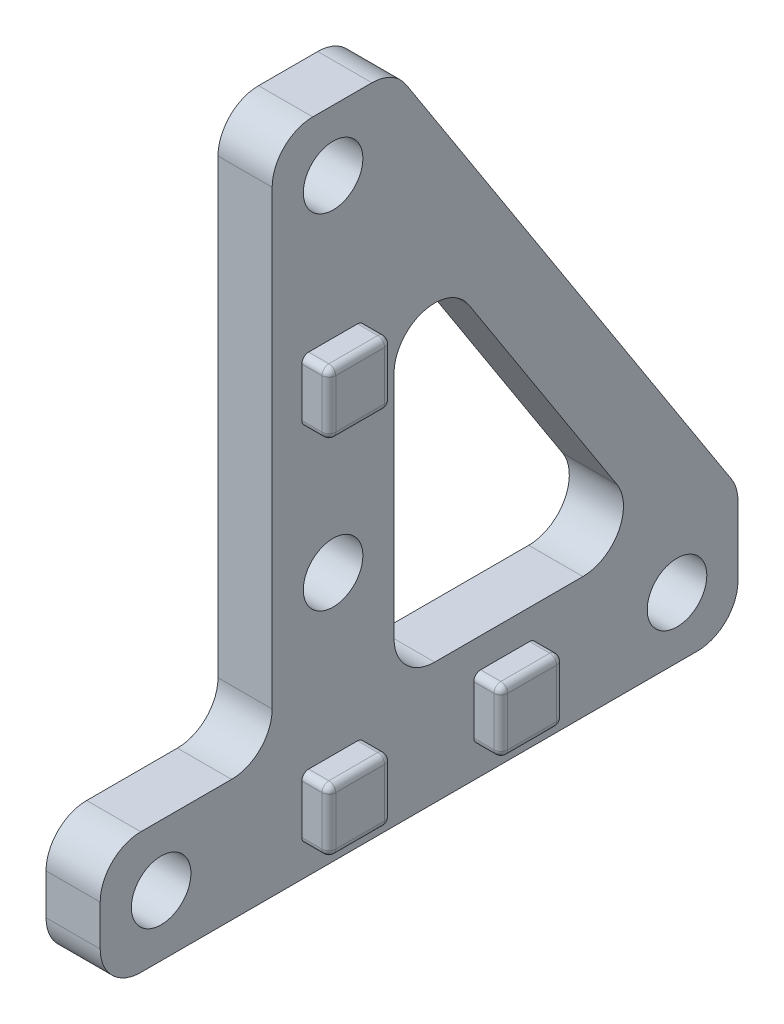
SolidWorks part; units mm, degrees
ref_plane "Front Plane" through (0, 0, 0) normal (0, 0, 1) x (1, 0, 0)
ref_plane "Top Plane" through (0, 0, 0) normal (0, 1, 0) x (1, 0, 0)
ref_plane "Right Plane" through (0, 0, 0) normal (1, 0, 0) x (0, 0, -1)
sketch "Sketch1" plane through (0, 0, 0) normal (1, 0, 0) x (0, 0, -1)
  line L0 (-4.5, 4.5) -> (-17.2, 4.5)
  line L1 (-17.2, 4.5) -> (-17.2, -4.5)
  line L2 (-17.2, -4.5) -> (29.9, -4.5)
  line L3 (29.9, -4.5) -> (29.9, 4.5)
  line L4 (29.9, 4.5) -> (4.5, 43.87)
  line L5 (4.5, 43.87) -> (-4.5, 43.87)
  line L6 (-4.5, 43.87) -> (-4.5, 4.5)
  line L7 (4.5, 4.5) -> (23.9497, 4.5)
  line L8 (23.9497, 4.5) -> (4.5, 34.6471)
  line L9 (4.5, 34.6471) -> (4.5, 4.5)
  circle A1 centre (25.4, 0) radius 2.2
  circle A2 centre (0, 13.97) radius 2.2
  circle A3 centre (0, 39.37) radius 2.2
  circle A4 centre (-12.7, 0) radius 2.2
  dimension "D1" = 4.4
  dimension "D2" = 12.7
  dimension "D3" = 25.4
  dimension "D4" = 13.97
  dimension "D5" = 25.4
  dimension "D6" = 4.5
  dimension "D7" = 4.5
  dimension "D8" = 4.5
  dimension "D9" = 9
  dimension "D10" = 4.5
  dimension "D11" = 4.5
  dimension "D12" = 9
  dimension "D13" = 9
  dimension "D14" = 5
extrude "Boss-Extrude1" add sketch "Sketch1" along normal blind 4
fillet "Fillet1" radius 3 10 edges at (2, 4.5, 4.5) (2, -4.5, 17.2) (2, 4.5, 17.2) (2, -4.5, -29.9) (2, 4.5, -29.9) (2, 43.87, -4.5) (2, 43.87, 4.5) (2, 4.5, -4.5) (2, 4.5, -23.9497) (2, 34.6471, -4.5)
sketch "Sketch2" plane through (4, 0, 0) normal (1, 0, 0) x (0, 0, -1)
  line L1 (2.3114, 2.3114) -> (-2.3114, 2.3114)
  line L2 (2.3114, 2.3114) -> (2.3114, -2.3114)
  line L3 (2.3114, -2.3114) -> (-2.3114, -2.3114)
  line L4 (-2.3114, 2.3114) -> (-2.3114, -2.3114)
  line L5 (2.3114, 2.3114) -> (-2.3114, -2.3114) construction
  line L6 (2.3114, -2.3114) -> (-2.3114, 2.3114) construction
  line L7 (15.0114, 2.3114) -> (10.3886, 2.3114)
  line L8 (15.0114, 2.3114) -> (15.0114, -2.3114)
  line L9 (15.0114, -2.3114) -> (10.3886, -2.3114)
  line L10 (10.3886, 2.3114) -> (10.3886, -2.3114)
  line L11 (15.0114, 2.3114) -> (10.3886, -2.3114) construction
  line L12 (15.0114, -2.3114) -> (10.3886, 2.3114) construction
  line L13 (-2.3114, 28.9814) -> (2.3114, 28.9814)
  line L14 (-2.3114, 28.9814) -> (-2.3114, 24.3586)
  line L15 (-2.3114, 24.3586) -> (2.3114, 24.3586)
  line L16 (2.3114, 28.9814) -> (2.3114, 24.3586)
  line L17 (-2.3114, 28.9814) -> (2.3114, 24.3586) construction
  line L18 (-2.3114, 24.3586) -> (2.3114, 28.9814) construction
  point P0 (0, 0)
  point P6 (12.7, 0)
  point P11 (0, 26.67)
  point P16 (0, 13.97)
  point P17 (0, 0)
  point P19 (0, 0)
  dimension "D1" = 12.7
  dimension "D2" = 12.7
  dimension "D3" = 4.6228
extrude "Boss-Extrude2" add sketch "Sketch2" along normal blind 2
fillet "Fillet2" radius 0.508 12 edges at (5, 2.3114, -15.0114) (5, 2.3114, -10.3886) (5, -2.3114, -10.3886) (5, -2.3114, -15.0114) (5, -2.3114, -2.3114) (5, 2.3114, -2.3114) (5, 2.3114, 2.3114) (5, -2.3114, 2.3114) (5, 28.9814, 2.3114) (5, 28.9814, -2.3114) (5, 24.3586, -2.3114) (5, 24.3586, 2.3114)
fillet "Fillet3" radius 0.508 24 edges at (6, -2.1626, -10.5374) (6, 0, -10.3886) (6, 2.1626, -10.5374) (6, 2.3114, -12.7) (6, 2.1626, -14.8626) (6, 0, -15.0114) (6, -2.1626, -14.8626) (6, -2.1626, 2.1626) (6, 0, 2.3114) (6, 2.1626, 2.1626) (6, 2.3114, 0) (6, 2.1626, -2.1626) (6, 0, -2.3114) (6, -2.1626, -2.1626) (6, 24.5074, 2.1626) (6, 26.67, 2.3114) (6, 28.8326, 2.1626) (6, 28.9814, 0) (6, 28.8326, -2.1626) (6, 26.67, -2.3114) (6, 24.5074, -2.1626) (6, -2.3114, -12.7) (6, -2.3114, 0) (6, 24.3586, 0)
